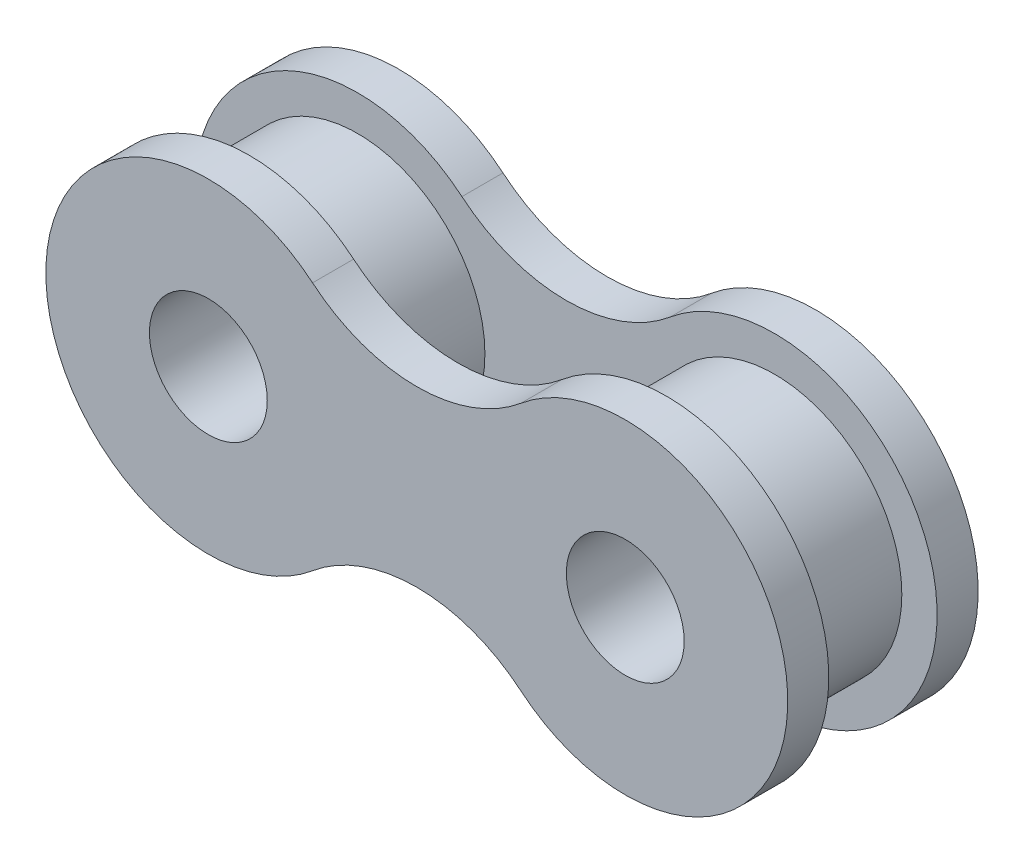
SolidWorks part; units mm, degrees
ref_plane "Спереди" through (0, 0, 0) normal (0, 0, 1) x (1, 0, 0)
ref_plane "Сверху" through (0, 0, 0) normal (0, 1, 0) x (1, 0, 0)
ref_plane "Справа" through (0, 0, 0) normal (1, 0, 0) x (0, 0, -1)
sketch "Эскиз1" plane through (0, 0, 0) normal (0, 0, 1) x (1, 0, 0)
  line L0 (-12.9643, 0) -> (25.4438, 0) construction
  line L1 (0, 0) -> (0, 11.9293) construction
  line L2 (-6.35, -4.9488) -> (15.0678, -4.9488) construction
  arc A0 (3.175, -8.7464) -> (3.175, -1.1512) centre (6.35, -4.9488) ccw
  arc A1 (-3.175, -8.7464) -> (-3.175, -1.1512) centre (-6.35, -4.9488) cw
  arc A2 (-3.175, -1.1512) -> (3.175, -1.1512) centre (0, 2.6465) ccw
  arc A3 (-3.175, -8.7464) -> (3.175, -8.7464) centre (0, -12.544) cw
  circle A4 centre (-6.35, -4.9488) radius 1.795
  circle A5 centre (6.35, -4.9488) radius 1.795
  circle A6 centre (-6.35, -4.9488) radius 3.875
  circle A7 centre (6.35, -4.9488) radius 3.875
  point P9 (6.2397, 0)
  dimension "D1" = 9.9
  dimension "D3" = 4.95
  dimension "D4" = 3.59
  dimension "D5" = 7.75
  dimension "D2" = 12.7
ref_plane "Плоскость2" through (0, 0, 2.9) normal (0, 0, 1) x (1, 0, 0)
sketch "Эскиз4" plane through (0, 0, 2.9) normal (0, 0, 1) x (1, 0, 0)
  circle A1 centre (6.35, -4.9488) radius 1.795
  circle A2 centre (6.35, -4.9488) radius 1.795
  circle A3 centre (-6.35, -4.9488) radius 1.795
  circle A4 centre (-6.35, -4.9488) radius 1.795
  circle A5 centre (6.35, -4.9488) radius 3.875
  circle A6 centre (6.35, -4.9488) radius 3.875
  circle A7 centre (-6.35, -4.9488) radius 3.875
  circle A8 centre (-6.35, -4.9488) radius 3.875
  arc A12 (3.175, -8.7464) -> (3.175, -1.1512) centre (6.35, -4.9488) ccw
  arc A13 (-3.175, -1.1512) -> (3.175, -1.1512) centre (0, 2.6465) ccw
  arc A14 (-3.175, -1.1512) -> (-3.175, -8.7464) centre (-6.35, -4.9488) ccw
  arc A15 (3.175, -8.7464) -> (-3.175, -8.7464) centre (0, -12.544) ccw
  arc A16 (3.175, -8.7464) -> (3.175, -1.1512) centre (6.35, -4.9488) ccw
  arc A17 (-3.175, -1.1512) -> (3.175, -1.1512) centre (0, 2.6465) ccw
  arc A18 (-3.175, -1.1512) -> (-3.175, -8.7464) centre (-6.35, -4.9488) ccw
  arc A19 (3.175, -8.7464) -> (-3.175, -8.7464) centre (0, -12.544) ccw
  dimension "D1" = 0
  dimension "D2" = 0
  dimension "D3" = 0
  dimension "D4" = 0
  dimension "D5" = 0
extrude "Бобышка-Вытянуть3" add sketch "Эскиз4" against normal blind 1.25 contours A19 A16 A17 A18 A8 A6 | A8 A4 | A6 A2
mirror "Зеркальное отражение6" about plane through (0, 0, 0) normal (0, 0, 1) of bodies 107
extrude "Бобышка-Вытянуть4" add sketch "Эскиз1" along normal up to next (1.65 mm away) and the other way up to next (2.9 mm away) contours A6 | A4 | A5 | A7
equation "\"t shag\"= 12.7'b"
equation "\"b1\"= 3.3"
equation "\"d1\"= 7.75"
equation "\"b2\"= 5.8"
equation "\"d2\"= 3.59"
equation "\"g\"= 9.9"
equation "\"a1\"= 10.2"
equation "\"k\"= 1.5"
equation "\"D1@Эскиз1\"=\"g\""
equation "\"D2@Эскиз1\"=\"t shag\""
equation "\"D3@Эскиз1\"=\"g\"/2"
equation "\"D4@Эскиз1\"=\"d2\""
equation "\"D5@Эскиз1\"=\"d1\""
equation "\"D1@Плоскость2\"= \"b2\" / 2"
equation "\"D1@Бобышка-Вытянуть3\"= ( \"b2\" - \"b1\" ) / 2"
